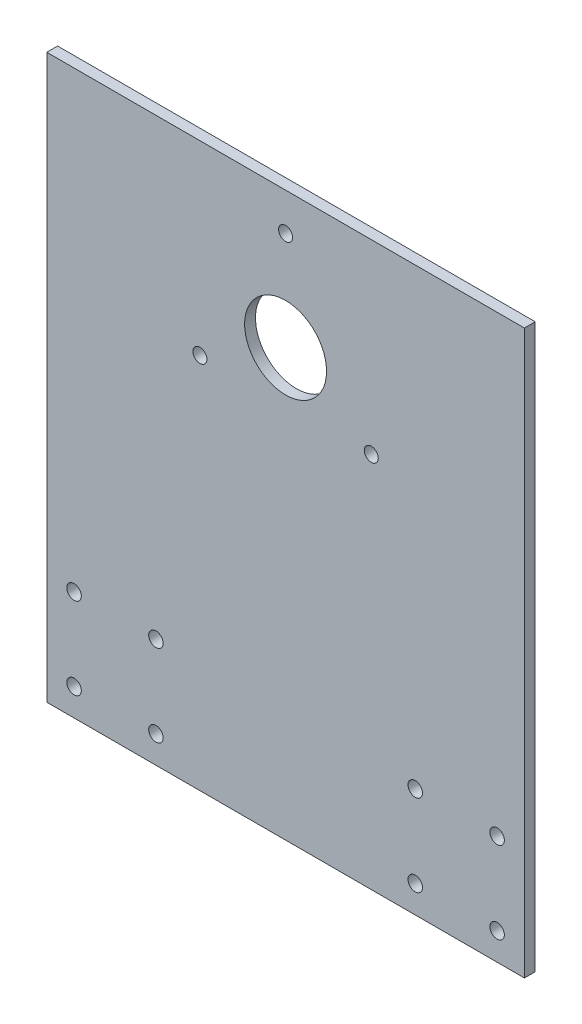
SolidWorks part; units mm, degrees
ref_plane "Front Plane" through (0, 0, 0) normal (0, 0, 1) x (1, 0, 0)
ref_plane "Top Plane" through (0, 0, 0) normal (0, 1, 0) x (1, 0, 0)
ref_plane "Right Plane" through (0, 0, 0) normal (1, 0, 0) x (0, 0, -1)
sketch "Sketch1" plane through (0, 0, 0) normal (0, 0, 1) x (1, 0, 0)
  line L0 (0, 82.5) -> (0, -82.5) construction
  line L1 (-70, -82.5) -> (70, -82.5)
  line L2 (-70, -82.5) -> (-70, 82.5)
  line L3 (-70, 82.5) -> (70, 82.5)
  line L4 (70, -82.5) -> (70, 82.5)
  line L5 (-70, -82.5) -> (70, 82.5) construction
  line L6 (-70, 82.5) -> (70, -82.5) construction
  line L7 (-50, -78.3304) -> (-50, -60.5714) construction
  line L10 (-62, -62.5) -> (-36.3402, -62.5) construction
  circle A0 centre (0, 42.5) radius 33.35 construction
  circle A1 centre (0, 42.5) radius 29 construction
  circle A2 centre (0, 71.5) radius 2.05
  circle A3 centre (25.1147, 28) radius 2.05
  circle A4 centre (-25.1147, 28) radius 2.05
  circle A10 centre (0, 42.5) radius 12
  circle A11 centre (-62, -74.5) radius 2.125
  circle A12 centre (-38, -74.5) radius 2.125
  circle A13 centre (-38, -50.5) radius 2.125
  circle A14 centre (-62, -50.5) radius 2.125
  circle A15 centre (38, -74.5) radius 2.125
  circle A16 centre (62, -74.5) radius 2.125
  circle A17 centre (62, -50.5) radius 2.125
  circle A18 centre (38, -50.5) radius 2.125
  point P0 (0, 0)
  point P19 (0, 42.5)
  dimension "D3" = 66.7
  dimension "D4" = 40
  dimension "D5" = 58
  dimension "D6" = 4.1
  dimension "D8" = 4.25
  dimension "D9" = 8
  dimension "D10" = 8
  dimension "D12" = 24
  dimension "D1" = 140
  dimension "D2" = 165
  dimension "D11" = 12
  dimension "D13" = 12
  dimension "D7" = 3
extrude "Boss-Extrude1" add sketch "Sketch1" along normal blind 3.175
